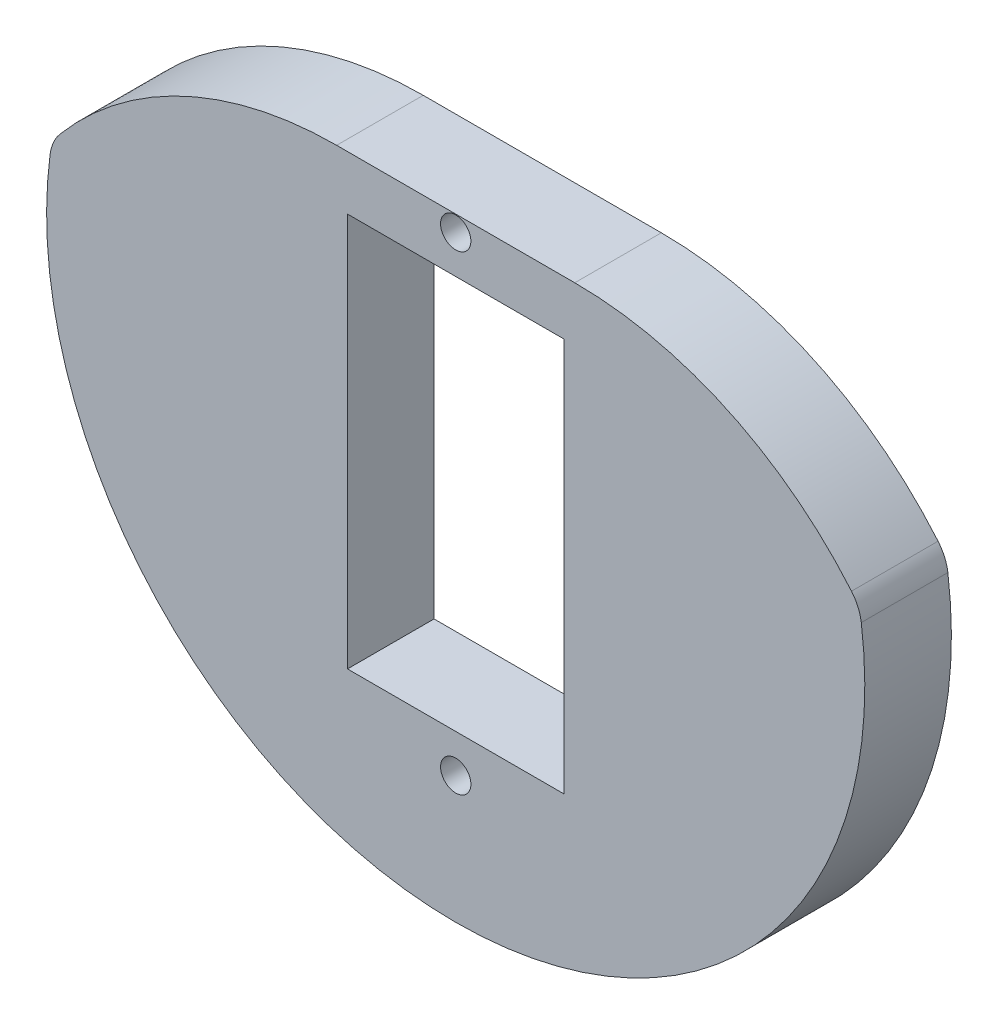
SolidWorks part; units mm, degrees
material "ABS"
ref_plane "Front Plane" through (0, 0, 0) normal (0, 0, 1) x (1, 0, 0)
ref_plane "Top Plane" through (0, 0, 0) normal (0, 1, 0) x (1, 0, 0)
ref_plane "Right Plane" through (0, 0, 0) normal (1, 0, 0) x (0, 0, -1)
sketch "Sketch1" plane through (0, 0, 0) normal (0, 0, 1) x (1, 0, 0)
  line L0 (0, -24.003) -> (0, 11.9888) construction
  line L1 (-6.985, 11.9888) -> (6.985, 11.9888)
  arc A0 (-23.6905, 3.8608) -> (23.6905, 3.8608) centre (0, 0) ccw
  arc A1 (6.985, 11.9888) -> (23.6905, 3.8608) centre (6.985, -9.2426) cw
  arc A2 (-6.985, 11.9888) -> (-23.6905, 3.8608) centre (-6.985, -9.2426) ccw
  point P8 (0, 11.9888)
  dimension "D1" = 48.006
  dimension "D2" = 35.9918
  dimension "D3" = 13.97
  dimension "D4" = 8.128
extrude "Boss-Extrude1" add sketch "Sketch1" along normal blind 5.08
fillet "Fillet1" radius 2.54 2 edges at (-23.6905, 3.8608, 2.54) (23.6905, 3.8608, 2.54)
sketch "Sketch5" plane through (0, 0, 5.08) normal (0, 0, 1) x (1, 0, 0)
  line L0 (6.985, 11.9888) -> (-6.985, 11.9888) construction
  line L1 (-6.35, 8.8138) -> (6.35, 8.8138)
  line L2 (-6.35, 8.8138) -> (-6.35, -14.3002)
  line L3 (-6.35, -14.3002) -> (6.35, -14.3002)
  line L4 (6.35, 8.8138) -> (6.35, -14.3002)
  line L5 (0, -24.003) -> (0, -43.561) construction
  line L6 (0, -43.561) -> (0, 2.4638) construction
  line L7 (0, 10.1664) -> (0, -15.6527) construction
  arc A0 (-23.7978, 3.1318) -> (23.7978, 3.1318) centre (0, 0) ccw construction
  circle A1 centre (0, 2.4638) radius 6.35 construction
  circle A2 centre (0, -16.5417) radius 0.889
  circle A3 centre (0, 11.0554) radius 0.889
  point P6 (0, 11.9888)
  point P7 (0, 8.8138)
  point P23 (0, -2.7432)
  point P24 (6.35, -2.7432)
  dimension "D5" = 1.778
  dimension "D1" = 19.558
  dimension "D2" = 46.0248
  dimension "D3" = 23.114
  dimension "D4" = 12.7
  dimension "D6" = 25.8191
extrude "Cut-Extrude1" cut sketch "Sketch5" against normal through all
